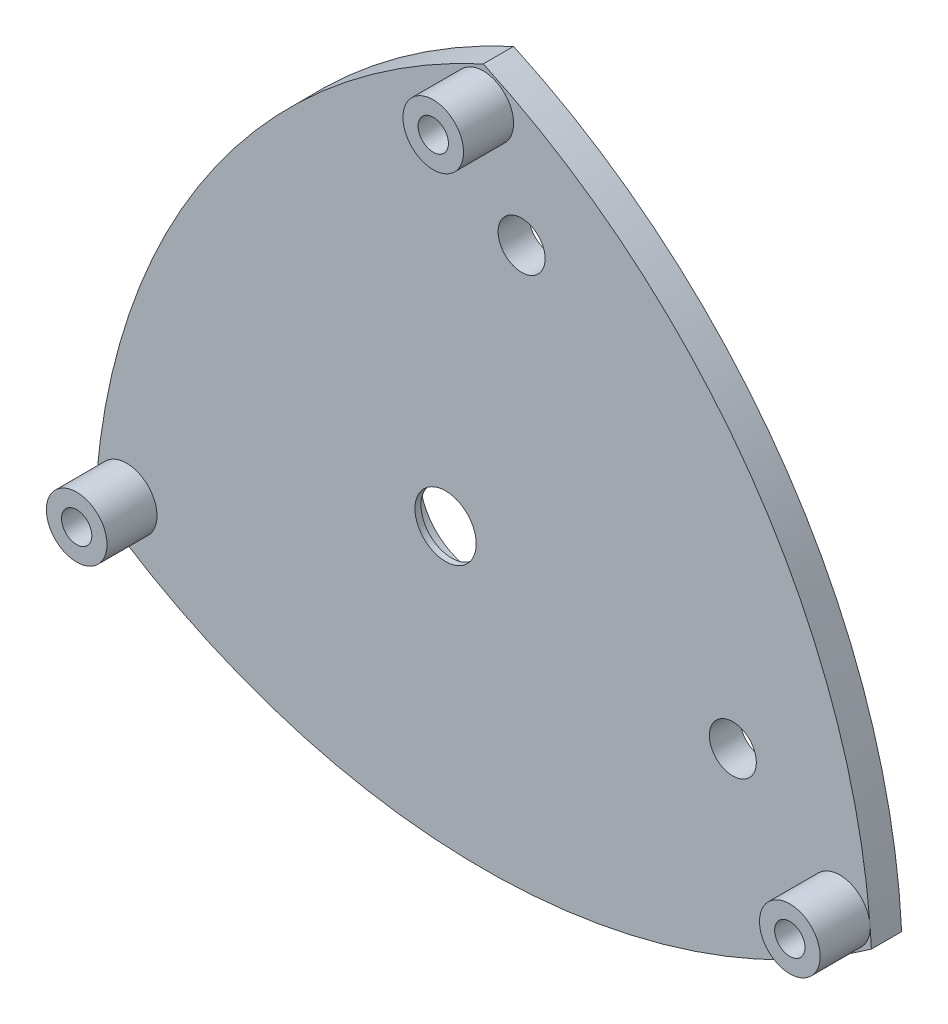
SolidWorks part; units mm, degrees
ref_plane "前视基准面" through (0, 0, 0) normal (0, 0, 1) x (1, 0, 0)
ref_plane "上视基准面" through (0, 0, 0) normal (0, 1, 0) x (1, 0, 0)
ref_plane "右视基准面" through (0, 0, 0) normal (1, 0, 0) x (0, 0, -1)
sketch "草图1" plane through (0, 0, 0) normal (0, 0, 1) x (1, 0, 0)
  line L0 (0, -115) -> (0, 115) construction
  line L2 (0, 0) -> (-128.0227, -73.9139) construction
  line L3 (0, 0) -> (128.0227, -73.9139) construction
  arc A5 (-128.0227, -73.9139) -> (0, 115) centre (91.6989, -84.9783) cw
  arc A6 (-128.0227, -73.9139) -> (128.0227, -73.9139) centre (0, 105) ccw
  arc A7 (128.0227, -73.9139) -> (0, 115) centre (-91.6989, -84.9783) ccw
  circle A8 centre (0, 103) radius 5
  circle A9 centre (-117.6304, -67.9139) radius 5
  circle A10 centre (117.6304, -67.9139) radius 5
  point P8 (-117.6304, -67.9139)
  point P11 (0, 103)
  point P12 (117.6304, -67.9139)
  point P14 (0, 0)
  dimension "D1" = 220
  dimension "D7" = 10
  dimension "D8" = 10
  dimension "D9" = 10
  dimension "D2" = 12
  dimension "D3" = 12
  dimension "D4" = 12
  dimension "D5" = 120
  dimension "D6" = 230
extrude "凸台-拉伸1" add sketch "草图1" along normal blind 10
sketch "草图2" plane through (0, 0, 10) normal (0, 0, 1) x (1, 0, 0)
  circle A0 centre (0, 103) radius 5
  circle A1 centre (0, 103) radius 10
  circle A2 centre (-117.6304, -67.9139) radius 5
  circle A3 centre (-117.6304, -67.9139) radius 10
  circle A4 centre (117.6304, -67.9139) radius 5
  circle A5 centre (117.6304, -67.9139) radius 10
  dimension "D1" = 20
  dimension "D2" = 20
  dimension "D3" = 20
extrude "凸台-拉伸2" add sketch "草图2" along normal blind 16.5
sketch "草图3" plane through (0, 0, 0) normal (0, 0, -1) x (-1, 0, 0)
  circle A0 centre (-12.651, 69.5155) radius 7.75
  circle A1 centre (-82.3341, -39.5307) radius 7.75
  circle A2 centre (12.4289, -23.2988) radius 15
  dimension "D1" = 15.5
  dimension "D2" = 15.5
  dimension "D4" = 39.5307
  dimension "D5" = 69.5155
  dimension "D6" = 12.651
  dimension "D7" = 12.4289
  dimension "D3" = 82.3341
extrude "切除-拉伸1" cut sketch "草图3" against normal blind 15
sketch "草图5" plane through (0, 0, 0) normal (0, 0, -1) x (-1, 0, 0)
  circle A0 centre (12.4289, -23.2988) radius 18.5
  dimension "D1" = 37
extrude "切除-拉伸3" cut sketch "草图5" against normal blind 10
sketch "草图6" plane through (0, 0, 10) normal (0, 0, 1) x (1, 0, 0)
  circle A0 centre (-12.4289, -23.2988) radius 18.5
extrude "凸台-拉伸3" add sketch "草图6" against normal blind 2
sketch "草图7" plane through (0, 0, 8) normal (0, 0, -1) x (-1, 0, 0)
  circle A0 centre (12.4289, -23.2988) radius 10.1
  dimension "D1" = 20.2
extrude "切除-拉伸4" cut sketch "草图7" against normal blind 8
